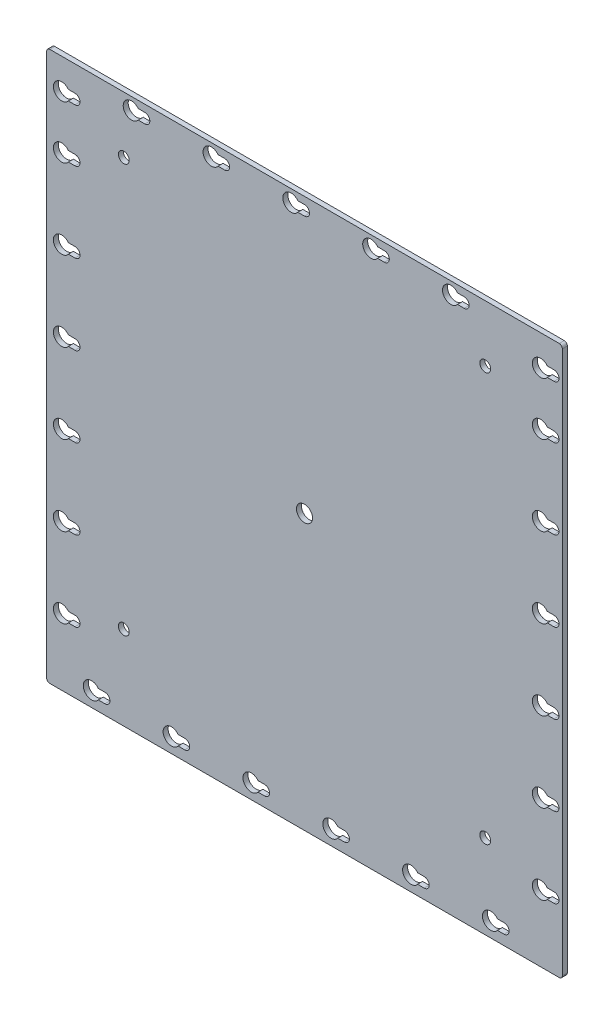
SolidWorks part; units mm, degrees
material "6061 Alloy"
ref_plane "Front Plane" through (0, 0, 0) normal (0, 0, 1) x (1, 0, 0)
ref_plane "Top Plane" through (0, 0, 0) normal (0, 1, 0) x (1, 0, 0)
ref_plane "Right Plane" through (0, 0, 0) normal (1, 0, 0) x (0, 0, -1)
sketch "Sketch1" plane through (0, 0, 0) normal (0, 0, 1) x (1, 0, 0)
  line L0 (0, 0) -> (0, -174.745)
  line L3 (0, -174.745) -> (165.1, -174.745)
  line L5 (0, 0) -> (165.1, 0)
  line L6 (165.1, -174.745) -> (165.1, 0)
  line L7 (82.55, 0) -> (82.55, -174.745) construction
  line L8 (31.75, -2.2625) -> (29.6344, -2.2625)
  line L9 (31.75, -5.4375) -> (29.6344, -5.4375)
  line L10 (9.525, -24.9325) -> (7.4094, -24.9325)
  line L11 (9.525, -28.1075) -> (7.4094, -28.1075)
  line L12 (161.925, -24.9325) -> (159.8094, -24.9325)
  line L13 (161.925, -28.1075) -> (159.8094, -28.1075)
  line L14 (57.15, -2.2625) -> (55.0344, -2.2625)
  line L15 (57.15, -5.4375) -> (55.0344, -5.4375)
  line L16 (82.55, -2.2625) -> (80.4344, -2.2625)
  line L17 (82.55, -5.4375) -> (80.4344, -5.4375)
  line L18 (107.95, -2.2625) -> (105.8344, -2.2625)
  line L19 (107.95, -5.4375) -> (105.8344, -5.4375)
  line L20 (133.35, -2.2625) -> (131.2344, -2.2625)
  line L21 (133.35, -5.4375) -> (131.2344, -5.4375)
  line L22 (9.525, -50.3325) -> (7.4094, -50.3325)
  line L23 (9.525, -53.5075) -> (7.4094, -53.5075)
  line L24 (161.925, -50.3325) -> (159.8094, -50.3325)
  line L25 (161.925, -53.5075) -> (159.8094, -53.5075)
  line L26 (9.525, -75.7325) -> (7.4094, -75.7325)
  line L27 (9.525, -78.9075) -> (7.4094, -78.9075)
  line L28 (161.925, -75.7325) -> (159.8094, -75.7325)
  line L29 (161.925, -78.9075) -> (159.8094, -78.9075)
  line L30 (9.525, -101.1325) -> (7.4094, -101.1325)
  line L31 (9.525, -104.3075) -> (7.4094, -104.3075)
  line L32 (161.925, -101.1325) -> (159.8094, -101.1325)
  line L33 (161.925, -104.3075) -> (159.8094, -104.3075)
  line L34 (9.525, -126.5325) -> (7.4094, -126.5325)
  line L35 (9.525, -129.7075) -> (7.4094, -129.7075)
  line L36 (161.925, -126.5325) -> (159.8094, -126.5325)
  line L37 (161.925, -129.7075) -> (159.8094, -129.7075)
  line L38 (9.525, -151.9325) -> (7.4094, -151.9325)
  line L39 (9.525, -155.1075) -> (7.4094, -155.1075)
  line L40 (161.925, -151.9325) -> (159.8094, -151.9325)
  line L41 (161.925, -155.1075) -> (159.8094, -155.1075)
  line L42 (19.05, -168.395) -> (16.9344, -168.395)
  line L43 (19.05, -171.57) -> (16.9344, -171.57)
  line L44 (44.45, -168.395) -> (42.3344, -168.395)
  line L45 (44.45, -171.57) -> (42.3344, -171.57)
  line L46 (69.85, -168.395) -> (67.7344, -168.395)
  line L47 (69.85, -171.57) -> (67.7344, -171.57)
  line L48 (95.25, -168.395) -> (93.1344, -168.395)
  line L49 (95.25, -171.57) -> (93.1344, -171.57)
  line L50 (120.65, -168.395) -> (118.5344, -168.395)
  line L51 (120.65, -171.57) -> (118.5344, -171.57)
  line L52 (146.05, -168.395) -> (143.9344, -168.395)
  line L53 (146.05, -171.57) -> (143.9344, -171.57)
  line L54 (0.5, 0) -> (0.5, -174.745)
  line L55 (164.6, -174.745) -> (164.6, 0)
  line L56 (0.5, -174.745) -> (164.6, -174.745)
  line L57 (9.525, -8.1) -> (7.4094, -8.1)
  line L58 (9.525, -11.275) -> (7.4094, -11.275)
  line L59 (161.925, -8.1) -> (159.8094, -8.1)
  line L60 (161.925, -11.275) -> (159.8094, -11.275)
  circle A41 centre (9.525, -153.52) radius 1.5875
  circle A42 centre (19.05, -169.9825) radius 1.5875
  circle A43 centre (9.525, -128.12) radius 1.5875
  circle A44 centre (9.525, -102.72) radius 1.5875
  circle A45 centre (9.525, -77.32) radius 1.5875
  circle A46 centre (9.525, -51.92) radius 1.5875
  circle A47 centre (9.525, -26.52) radius 1.5875
  circle A49 centre (44.45, -169.9825) radius 1.5875
  circle A50 centre (69.85, -169.9825) radius 1.5875
  circle A51 centre (95.25, -169.9825) radius 1.5875
  circle A52 centre (120.65, -169.9825) radius 1.5875
  circle A68 centre (146.05, -169.9825) radius 1.5875
  circle A69 centre (107.95, -3.85) radius 1.5875
  circle A70 centre (82.55, -3.85) radius 1.5875
  circle A71 centre (57.15, -3.85) radius 1.5875
  circle A72 centre (9.525, -1.12) radius 1.5875 [skipped]
  circle A73 centre (133.35, -3.85) radius 1.5875
  circle A74 centre (31.75, -3.85) radius 1.5875
  circle A75 centre (161.925, -26.52) radius 1.5875
  circle A76 centre (161.925, -51.92) radius 1.5875
  circle A77 centre (161.925, -77.32) radius 1.5875
  circle A78 centre (161.925, -102.72) radius 1.5875
  circle A79 centre (161.925, -128.12) radius 1.5875
  circle A80 centre (161.925, -153.52) radius 1.5875
  circle A81 centre (27.5125, -3.85) radius 2.65
  circle A83 centre (5.2875, -26.52) radius 2.65
  circle A84 centre (157.6875, -26.52) radius 2.65
  circle A85 centre (52.9125, -3.85) radius 2.65
  circle A86 centre (78.3125, -3.85) radius 2.65
  circle A87 centre (103.7125, -3.85) radius 2.65
  circle A88 centre (129.1125, -3.85) radius 2.65
  circle A89 centre (5.2875, -51.92) radius 2.65
  circle A90 centre (157.6875, -51.92) radius 2.65
  circle A91 centre (5.2875, -77.32) radius 2.65
  circle A92 centre (157.6875, -77.32) radius 2.65
  circle A93 centre (5.2875, -102.72) radius 2.65
  circle A94 centre (157.6875, -102.72) radius 2.65
  circle A95 centre (5.2875, -128.12) radius 2.65
  circle A96 centre (157.6875, -128.12) radius 2.65
  circle A97 centre (5.2875, -153.52) radius 2.65
  circle A98 centre (157.6875, -153.52) radius 2.65
  circle A99 centre (14.8125, -169.9825) radius 2.65
  circle A100 centre (40.2125, -169.9825) radius 2.65
  circle A101 centre (65.6125, -169.9825) radius 2.65
  circle A102 centre (91.0125, -169.9825) radius 2.65
  circle A103 centre (116.4125, -169.9825) radius 2.65
  circle A104 centre (141.8125, -169.9825) radius 2.65
  circle A105 centre (82.55, -87.3725) radius 2.5527
  circle A107 centre (9.525, -9.6875) radius 1.5875
  circle A108 centre (5.2875, -9.6875) radius 2.65
  circle A109 centre (161.925, -9.6875) radius 1.5875
  circle A110 centre (157.6875, -9.6875) radius 2.65
  dimension "D3" = 3.175
  dimension "D8" = 3.175
  dimension "D21" = 5.3
  dimension "D31" = 5.1054
  dimension "D33" = 5.3
  dimension "D1" = 165.1
  dimension "D2" = 174.745
  dimension "D5" = 9.525
  dimension "D4" = 21.225
  dimension "D6" = 19.05
  dimension "D7" = 4.7625
  dimension "D9" = 25.4
  dimension "D10" = 25.4
  dimension "D15" = 25.4
  dimension "D12" = 3.85
  dimension "D13" = 31.75
  dimension "D17" = 31.75
  dimension "D18" = 3.175
  dimension "D20" = 25.4
  dimension "D23" = 25.4
  dimension "D25" = 25.4
  dimension "D27" = 25.4
  dimension "D28" = 0.5
  dimension "D29" = 0.5
  dimension "D30" = 87.3725
  dimension "D34" = 16.8325
  dimension "D35" = 5.8375
  dimension "D11" = 7
  dimension "D14" = 5
  dimension "D16" = 5
  dimension "D19" = 6
  dimension "D22" = 5
  dimension "D24" = 6
  dimension "D26" = 6
extrude "Boss-Extrude1" add sketch "Sketch1" along normal blind 1.5875 contours L7 L5 L0 L3 A50 A41 A42 A43 A44 A45 A46 A47 A73 A49 | L5 L7 A70 A105 L56 L55 A84 L12 A75 L13 A87 L18 A69 L19 A88 L20 A73 L21 A90 L24 A76 L25 A92 L28 A77 L29 A94 L32 A78 L33 A96 L36 A79 L37 A98 L40 A80 L41 A102 L48
fillet "Fillet1" radius 1 4 edges at (164.6, 0, 0.7937) (164.6, -174.745, 0.7937) (0.5, -174.745, 0.7937) (0.5, 0, 0.7937)
sketch "Sketch2" plane through (0, 0, 1.5875) normal (0, 0, 1) x (1, 0, 0)
  line L0 (1.5, 0) -> (163.6, 0) construction
  line L1 (25.05, -18) -> (140.05, -18) construction
  line L2 (25.05, -18) -> (25.05, -148) construction
  line L3 (25.05, -148) -> (140.05, -148) construction
  line L4 (140.05, -18) -> (140.05, -148) construction
  line L5 (25.05, -18) -> (140.05, -148) construction
  line L6 (25.05, -148) -> (140.05, -18) construction
  circle A0 centre (25.05, -18) radius 1.725
  circle A1 centre (140.05, -18) radius 1.725
  circle A2 centre (140.05, -148) radius 1.725
  circle A3 centre (25.05, -148) radius 1.725
  point P4 (82.55, -83)
  point P11 (82.55, 0)
  point P12 (82.55, -86.0952)
  dimension "D1" = 3.45
  dimension "D2" = 115
  dimension "D3" = 130
  dimension "D4" = 18
extrude "Cut-Extrude1" cut sketch "Sketch2" against normal through all both
equation "\"D8@Sketch1\"=\"D3@Sketch1\""
equation "\"D29@Sketch1\"=\"D28@Sketch1\""
equation "\"D30@Sketch1\"=\"D2@Sketch1\"/2"
